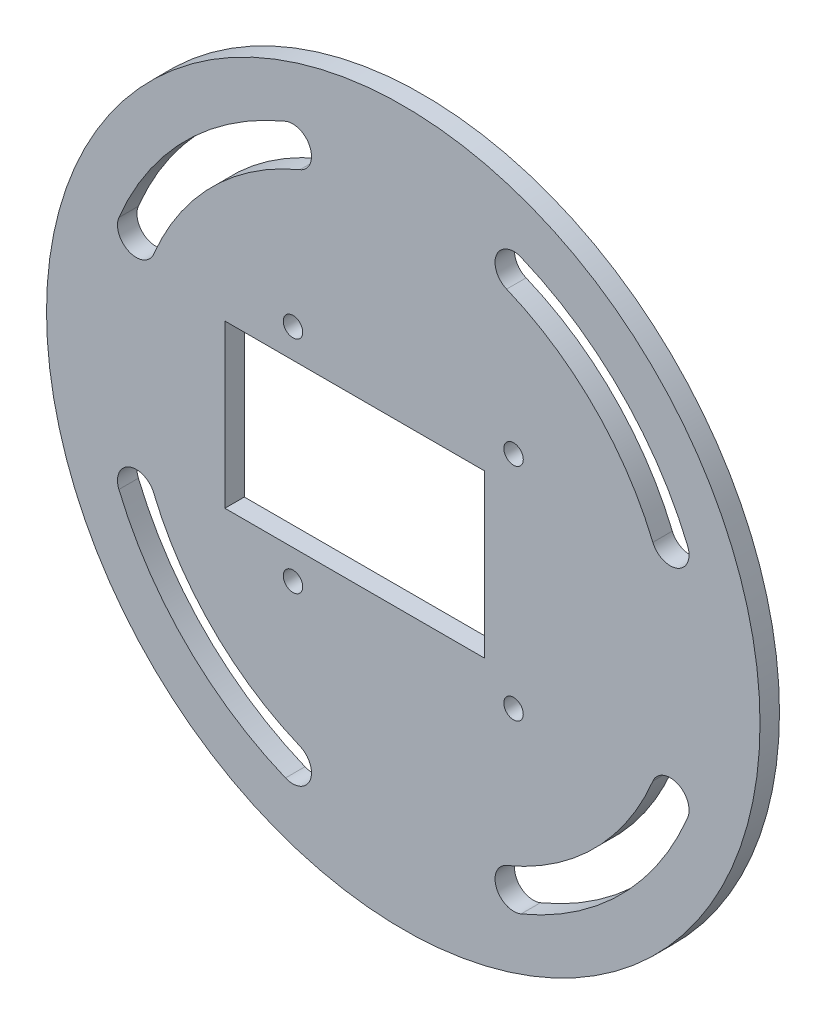
SolidWorks part; units mm, degrees
ref_plane "Front Plane" through (0, 0, 0) normal (0, 0, 1) x (1, 0, 0)
ref_plane "Top Plane" through (0, 0, 0) normal (0, 1, 0) x (1, 0, 0)
ref_plane "Right Plane" through (0, 0, 0) normal (1, 0, 0) x (0, 0, -1)
sketch "Sketch1" plane through (0, 0, 0) normal (0, 0, 1) x (1, 0, 0)
  circle A0 centre (0, 0) radius 55
  dimension "D1" = 110
extrude "Boss-Extrude1" add sketch "Sketch1" along normal blind 3
sketch "Sketch3" plane through (0, 0, 3) normal (0, 0, 1) x (1, 0, 0)
  line L0 (-31.5, 31.5) -> (-31.5, -31.5) construction
  line L5 (-17.0477, 41.1567) -> (41.1567, 17.0477) construction
  line L7 (-31.5, -31.5) -> (31.5, -31.5) construction
  line L8 (-31.5, 31.5) -> (31.5, 31.5) construction
  line L9 (31.5, 31.5) -> (31.5, -31.5) construction
  line L10 (0, 0) -> (0, 31.5) construction
  line L11 (0, 0) -> (-31.5, 0) construction
  line L12 (0, 0) -> (0, -31.5) construction
  line L13 (0, 0) -> (31.5, 0) construction
  line L14 (41.1567, 17.0477) -> (17.0477, -41.1567) construction
  line L15 (17.0477, -41.1567) -> (-41.1567, -17.0477) construction
  line L16 (-41.1567, -17.0477) -> (-17.0477, 41.1567) construction
  line L18 (-41.1567, 17.0477) -> (17.0477, 41.1567) construction
  line L19 (17.0477, 41.1567) -> (41.1567, -17.0477) construction
  line L20 (41.1567, -17.0477) -> (-17.0477, -41.1567) construction
  line L21 (-17.0477, -41.1567) -> (-41.1567, 17.0477) construction
  arc A75 (-15.9379, 38.4775) -> (-18.1575, 43.836) centre (-17.0477, 41.1567) ccw
  arc A77 (18.1575, 43.836) -> (15.9379, 38.4775) centre (17.0477, 41.1567) ccw
  arc A79 (38.4775, 15.9379) -> (43.836, 18.1575) centre (41.1567, 17.0477) ccw
  arc A81 (43.836, -18.1575) -> (38.4775, -15.9379) centre (41.1567, -17.0477) ccw
  arc A83 (15.9379, -38.4775) -> (18.1575, -43.836) centre (17.0477, -41.1567) ccw
  arc A85 (-18.1575, -43.836) -> (-15.9379, -38.4775) centre (-17.0477, -41.1567) ccw
  arc A87 (-38.4775, -15.9379) -> (-43.836, -18.1575) centre (-41.1567, -17.0477) ccw
  arc A89 (-43.836, 18.1575) -> (-38.4775, 15.9379) centre (-41.1567, 17.0477) ccw
  arc A91 (-43.836, -18.1575) -> (-18.1575, -43.836) centre (0, 0) ccw
  arc A92 (-38.4775, -15.9379) -> (-15.9379, -38.4775) centre (0, 0) ccw
  arc A93 (-18.1575, 43.836) -> (-43.836, 18.1575) centre (0, 0) ccw
  arc A94 (-15.9379, 38.4775) -> (-38.4775, 15.9379) centre (0, 0) ccw
  arc A95 (38.4775, 15.9379) -> (15.9379, 38.4775) centre (0, 0) ccw
  arc A96 (43.836, 18.1575) -> (18.1575, 43.836) centre (0, 0) ccw
  arc A97 (15.9379, -38.4775) -> (38.4775, -15.9379) centre (0, 0) ccw
  arc A98 (18.1575, -43.836) -> (43.836, -18.1575) centre (0, 0) ccw
  point P28 (0, 0)
  point P52 (0, 0)
  dimension "D2" = 63
extrude "Cut-Extrude1" cut sketch "Sketch3" against normal through all
sketch "Sketch4" plane through (0, 0, 3) normal (0, 0, 1) x (1, 0, 0)
  line L16 (-12.5, 12.5) -> (-27.5, 12.5)
  line L18 (0, 0) -> (0, 12.5) construction
  line L19 (0, 0) -> (0, -12.5) construction
  line L20 (12.5, -12.5) -> (-12.5, -12.5)
  line L21 (12.5, -12.5) -> (12.5, 12.5)
  line L22 (12.5, 12.5) -> (-12.5, 12.5)
  line L24 (12.5, -12.5) -> (-12.5, 12.5) construction
  line L25 (12.5, 12.5) -> (-12.5, -12.5) construction
  line L26 (-27.5, 12.5) -> (-27.5, -12.5)
  line L27 (-27.5, -12.5) -> (-12.5, -12.5)
  circle A0 centre (-17, 17) radius 1.5
  circle A1 centre (17, 17) radius 1.5
  circle A2 centre (17, -17) radius 1.5
  circle A3 centre (-17, -17) radius 1.5
  point P0 (0, 0)
  dimension "D3" = 3
  dimension "D4" = 2
  dimension "D1" = 25
  dimension "D2" = 12.5
  dimension "D6" = 12.5
  dimension "D7" = 15
  dimension "D5" = 2
extrude "Cut-Extrude2" cut sketch "Sketch4" against normal through all
